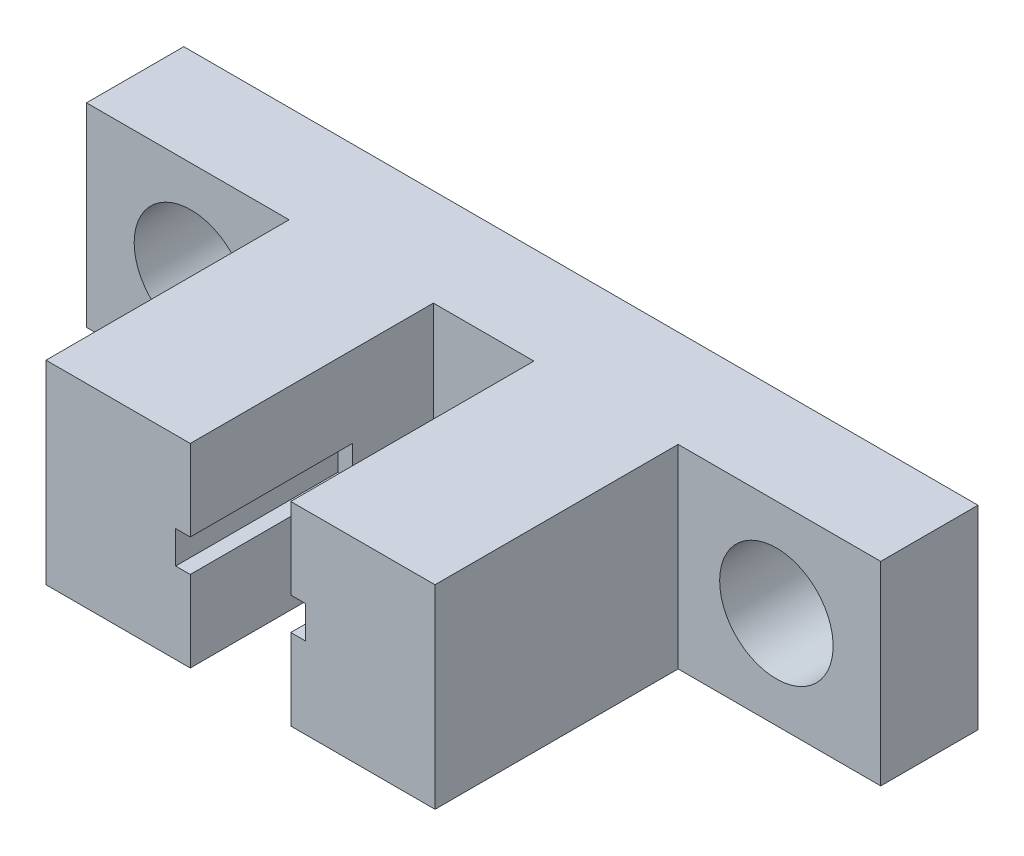
SolidWorks part; units mm, degrees
ref_plane "Front Plane" through (0, 0, 0) normal (0, 0, 1) x (1, 0, 0)
ref_plane "Top Plane" through (0, 0, 0) normal (0, 1, 0) x (1, 0, 0)
ref_plane "Right Plane" through (0, 0, 0) normal (1, 0, 0) x (0, 0, -1)
sketch "Sketch1" plane through (0, 0, 0) normal (0, 0, 1) x (1, 0, 0)
  line L0 (0, 0) -> (0, 12.8103)
  line L1 (-1.55, -4.8779) -> (-6, -4.8779)
  line L2 (-1.55, -4.8779) -> (-1.55, 1.1221)
  line L3 (-1.55, 1.1221) -> (-6, 1.1221)
  line L4 (-6, -4.8779) -> (-6, 1.1221)
  line L5 (-1.55, -4.8779) -> (-6, 1.1221) construction
  line L6 (-1.55, 1.1221) -> (-6, -4.8779) construction
  line L7 (1.55, 1.1221) -> (6, -4.8779) construction
  line L8 (1.55, -4.8779) -> (6, 1.1221) construction
  line L9 (6, -4.8779) -> (6, 1.1221)
  line L10 (1.55, 1.1221) -> (6, 1.1221)
  line L11 (1.55, -4.8779) -> (1.55, 1.1221)
  line L12 (1.55, -4.8779) -> (6, -4.8779)
  point P0 (-3.775, -1.8779)
  point P8 (0, 12.8103)
  point P13 (3.775, -1.8779)
  dimension "D1" = 3.1
  dimension "D2" = 6
  dimension "D3" = 12
  dimension "D4" = 4.45
extrude "Boss-Extrude1" add sketch "Sketch1" along normal blind 7.5 contours L4 L1 L2 L3 | L11 L12 L9 L10
sketch "Sketch2" plane through (0, 0, 0) normal (0, 0, -1) x (-1, 0, 0)
  line L0 (0, -1.8779) -> (0, 6.7079) construction
  line L1 (6, -4.8779) -> (-6, -4.8779)
  line L2 (6, -4.8779) -> (6, 1.1221)
  line L3 (6, 1.1221) -> (-6, 1.1221)
  line L4 (-6, -4.8779) -> (-6, 1.1221)
  line L5 (6, -4.8779) -> (-6, 1.1221) construction
  line L6 (6, 1.1221) -> (-6, -4.8779) construction
  line L7 (12.25, -4.8779) -> (-12.25, -4.8779)
  line L8 (12.25, -4.8779) -> (12.25, 1.1221)
  line L9 (12.25, 1.1221) -> (-12.25, 1.1221)
  line L10 (-12.25, -4.8779) -> (-12.25, 1.1221)
  line L11 (12.25, -4.8779) -> (-12.25, 1.1221) construction
  line L12 (12.25, 1.1221) -> (-12.25, -4.8779) construction
  line L13 (-5.8107, -4.8779) -> (-12.25, -4.8779)
  line L14 (-5.8107, -4.8779) -> (-5.8107, 1.1221)
  line L15 (-5.8107, 1.1221) -> (-12.25, 1.1221)
  line L16 (-12.25, -4.8779) -> (-12.25, 1.1221)
  line L17 (-5.8107, -4.8779) -> (-12.25, 1.1221) construction
  line L18 (-5.8107, 1.1221) -> (-12.25, -4.8779) construction
  circle A0 centre (-9.0303, -1.8779) radius 1.75
  circle A1 centre (9.0303, -1.8779) radius 1.75
  point P0 (0, -1.8779)
  point P6 (-9.0303, -1.8779)
  point P8 (0, -1.8779)
  line M15 (-1.55, -4.8779) -> (-1.55, 1.1221)
  line M16 (-1.55, 1.1221) -> (-6, 1.1221)
  line M17 (-6, 1.1221) -> (-6, -4.8779)
  line M18 (-6, -4.8779) -> (-1.55, -4.8779)
  dimension "D2" = 3.5
  dimension "D1" = 24.5
extrude "Boss-Extrude2" add sketch "Sketch2" along normal blind 3 contours L10 L7 L9 A0 M17 | L14 L7 M15 M16 | L14 L9 M18 M17 | L2 L3 L1 M15 | L8 L9 L2 L7 A1
sketch "Sketch3" plane through (0, 0, 7.5) normal (0, 0, 1) x (1, 0, 0)
  line L0 (6, -1.8779) -> (-4.6825, -1.8779) construction
  line L1 (-2, -1.3779) -> (2, -1.3779)
  line L2 (-2, -1.3779) -> (-2, -2.3779)
  line L3 (-2, -2.3779) -> (2, -2.3779)
  line L4 (2, -1.3779) -> (2, -2.3779)
  line L5 (-2, -1.3779) -> (2, -2.3779) construction
  line L6 (-2, -2.3779) -> (2, -1.3779) construction
  line L7 (6, -4.8779) -> (6, 1.1221) construction
  point P0 (0, -1.8779)
  point P5 (0, -1.8779)
  dimension "D1" = 1
  dimension "D2" = 4
extrude "Cut-Extrude1" cut sketch "Sketch3" against normal blind 5
sketch "Sketch4" plane through (-6, 0, 0) normal (-1, 0, 0) x (0, 0, 1)
  line L1 (14.5, -1.8779) -> (7.5, -1.8779) construction
  line L2 (7.5, -4.8779) -> (7.5, 1.1221) construction
  circle A1 centre (14.5, -1.8779) radius 13.5
  point P2 (0, 0)
  point P4 (7.5, -1.8779)
  point P7 (13.7384, -1.8779)
  dimension "D1" = 27
  dimension "D2" = 7
